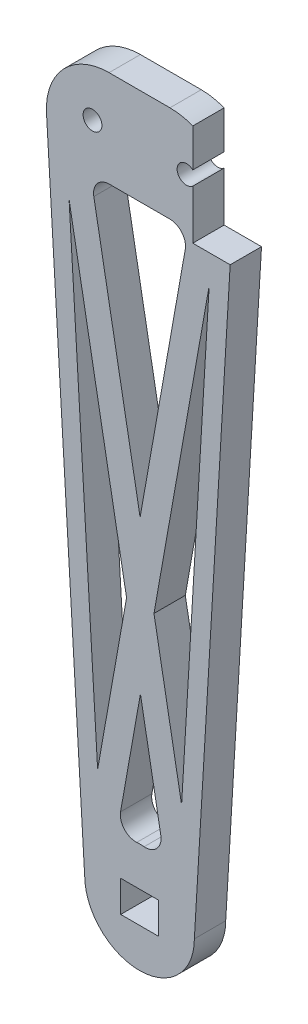
SolidWorks part; units mm, degrees
ref_plane "Front Plane" through (0, 0, 0) normal (0, 0, 1) x (1, 0, 0)
ref_plane "Top Plane" through (0, 0, 0) normal (0, 1, 0) x (1, 0, 0)
ref_plane "Right Plane" through (0, 0, 0) normal (1, 0, 0) x (0, 0, -1)
sketch "Sketch1" plane through (0, 0, 0) normal (0, 0, 1) x (1, 0, 0)
  line L0 (-30, 0) -> (30, 0)
  line L1 (0, 0) -> (15, 0)
  line L2 (55, 0) -> (-55, 0) construction
  line L3 (0, 0) -> (0, -210)
  line L4 (0, -44.7868) -> (0, 44.7868) construction
  line L5 (0, 0) -> (30, 0)
  line L6 (0, 0) -> (-30, 0)
  line L7 (0, 0) -> (-15, 0)
  line L8 (-6, -215) -> (6, -215)
  line L9 (-6, -215) -> (-6, -205)
  line L10 (-6, -205) -> (6, -205)
  line L11 (6, -215) -> (6, -205)
  line L12 (-6, -215) -> (6, -205) construction
  line L13 (-6, -205) -> (6, -215) construction
  line L14 (0, 0) -> (0, 15)
  line L15 (-30, 0) -> (-17.5, -210)
  line L16 (-30, 0) -> (30, 0)
  line L17 (-30, 0) -> (-30, 15.7704)
  line L18 (-30, 15.7704) -> (30, 15.7704)
  line L19 (30, 0) -> (30, 15.7704)
  line L20 (30, 0) -> (17.5, -210)
  circle A0 centre (15, 0) radius 3
  circle A1 centre (-15, 0) radius 3
  circle A2 centre (0, -210) radius 17.5
  point P4 (0, 0)
  dimension "D7" = 6
  dimension "D9" = 6
  dimension "D11" = 35
  dimension "D1" = 210
  dimension "D2" = 30
  dimension "D3" = 30
  dimension "D4" = 10
  dimension "D5" = 12
  dimension "D6" = 15
  dimension "D8" = 15
  dimension "D10" = 15
extrude "Boss-Extrude2" add sketch "Sketch1" along normal blind 10
fillet "Fillet1" radius 20 1 edges at (-30, 15.7704, 5)
fillet "Fillet2" radius 20 1 edges at (30, 15.7704, 5)
sketch "Sketch4" plane through (0, 0, 10) normal (0, 0, 1) x (1, 0, 0)
  line L0 (-29.3398, -11.0918) -> (-23.3398, -11.0918)
  line L1 (-29.6775, -5.418) -> (-17.5, -210) construction
  line L2 (29.3911, -10.23) -> (23.3911, -10.23)
  line L3 (29.6775, -5.418) -> (17.5, -210) construction
  line L4 (-18.3824, -195.1758) -> (-12.3824, -195.1758)
  line L5 (18.3824, -195.1758) -> (12.3824, -195.1758)
  line L6 (-12.3824, -195.1758) -> (-23.5439, -7.6624)
  line L7 (23.3911, -7.6624) -> (11.6198, -205.4193)
  line L8 (-22.9543, -15) -> (22.9543, -15)
  line L9 (-8.4362, -200.1287) -> (-16.4545, -196.0413)
  line L10 (9.2183, -200.015) -> (17.2308, -195.9163)
  line L11 (9.2183, -200.015) -> (-24.5465, -14.245)
  line L12 (17.2308, -195.9163) -> (-16.534, -10.1463)
  line L13 (-24.5465, -14.245) -> (-16.534, -10.1463)
  line L14 (-8.4362, -200.1287) -> (24.4903, -14.4152)
  line L15 (-16.4545, -196.0413) -> (16.472, -10.3277)
  line L16 (24.4903, -14.4152) -> (16.472, -10.3277)
  circle A0 centre (0, -210) radius 17.5
  circle A1 centre (15, 0) radius 15
  point P25 (0, -15)
  dimension "D5" = 15
  dimension "D1" = 6
  dimension "D2" = 6
  dimension "D3" = 6
  dimension "D4" = 6
  dimension "D6" = 9
  dimension "D7" = 9
extrude "Cut-Extrude1" cut sketch "Sketch4" against normal blind 10 contours L12 L15 L8 | L6 L15 L11 | L14 L12 L7 | A0 L11 L14
fillet "Fillet3" radius 5 4 edges at (8.2256, -194.5537, 5) (-7.3724, -194.1287, 5) (-15.6518, -15, 5) (15.6436, -15, 5)
sketch "Sketch5" plane through (0, 0, 10) normal (0, 0, 1) x (1, 0, 0)
  line L0 (15, 0) -> (30, 0)
  line L1 (55, 0) -> (-55, 0) construction
  line L2 (30, 0) -> (30, -20)
  line L3 (0, -175.7959) -> (34.2041, -175.7959)
  line L5 (30, -20) -> (30, 16.6458)
  line L6 (30, 16.6458) -> (17, 16.6458)
  line L8 (0, -175.7959) -> (-19.536, -175.7959)
  line L9 (-29.6775, -5.418) -> (-17.5, -210) construction
  line L11 (17, -20) -> (17, -18)
  line L13 (17, -18) -> (30.4933, -18)
  line L14 (17, -18) -> (17, 17.0491)
  line L15 (17, 17.0491) -> (30.4933, 17.0491)
  line L16 (30.4933, -18) -> (30.4933, 17.0491)
  circle A0 centre (0, -210) radius 30
  circle A1 centre (0, -210) radius 34.2041
  circle A2 centre (0, -210) radius 36
  line M1 (17.5, -210) -> (29.6775, -5.418)
  arc M2 (29.6775, -5.418) -> (9.7128, 15.7704) centre (9.7128, -4.2296) ccw
  circle M7 centre (15, 0) radius 3
  dimension "D3" = 60
  dimension "D4" = 36
  dimension "D1" = 15
  dimension "D2" = 20
  dimension "D5" = 2
extrude "Cut-Extrude4" cut sketch "Sketch5" against normal blind 10 contours L14 L13 L0 M1 M2 M7 | L14 L0 M7 M2
